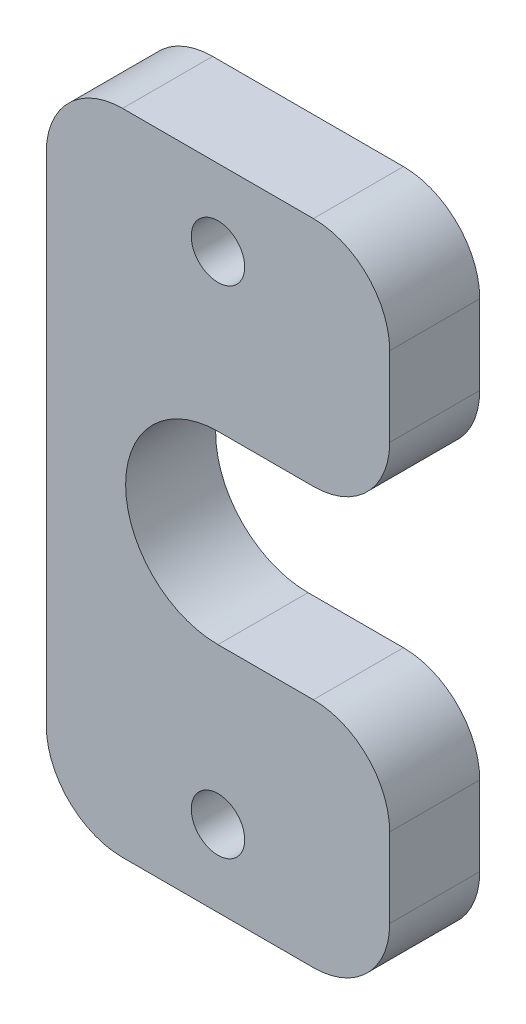
SolidWorks part; units mm, degrees
ref_plane "前视基准面" through (0, 0, 0) normal (0, 0, 1) x (1, 0, 0)
ref_plane "上视基准面" through (0, 0, 0) normal (0, 1, 0) x (1, 0, 0)
ref_plane "右视基准面" through (0, 0, 0) normal (1, 0, 0) x (0, 0, -1)
sketch "草图1" plane through (0, 0, 0) normal (0, 0, 1) x (1, 0, 0)
  line B0 (-11.25, 16.25) -> (-11.25, -16.25)
  line B1 (11.25, 16.25) -> (11.25, 11.05)
  line B2 (11.25, -11.05) -> (11.25, -16.25)
  line B3 (-6.25, 21.25) -> (6.25, 21.25)
  line B4 (-6.25, -21.25) -> (6.25, -21.25)
  line B5 (0, 6.05) -> (6.25, 6.05)
  line B6 (0, -6.05) -> (6.25, -6.05)
  arc B7 (6.25, 6.05) -> (11.25, 11.05) centre (6.25, 11.05) ccw
  arc B8 (11.25, -11.05) -> (6.25, -6.05) centre (6.25, -11.05) ccw
  circle B9 centre (0, 16.25) radius 1.75
  arc B10 (-6.25, 21.25) -> (-11.25, 16.25) centre (-6.25, 16.25) ccw
  arc B11 (11.25, 16.25) -> (6.25, 21.25) centre (6.25, 16.25) ccw
  circle B12 centre (0, -16.25) radius 1.75
  arc B13 (-11.25, -16.25) -> (-6.25, -21.25) centre (-6.25, -16.25) ccw
  arc B14 (6.25, -21.25) -> (11.25, -16.25) centre (6.25, -16.25) ccw
  arc B15 (0, 6.05) -> (0, -6.05) centre (0, 0) ccw
sketch_block_instance "块1-1"
sketch_block "块1"
extrude "凸台-拉伸1" add sketch "草图1" along normal blind 5.9
sketch "草图2" plane through (0, 0, 0) normal (0, 0, -1) x (-1, 0, 0)
  line L1 (1.6454, 13.4) -> (3.2909, 16.25)
  line L2 (3.2909, 16.25) -> (1.6454, 19.1)
  line L3 (1.6454, 19.1) -> (-1.6454, 19.1)
  line L4 (-1.6454, 19.1) -> (-3.2909, 16.25)
  line L5 (-3.2909, 16.25) -> (-1.6454, 13.4)
  line L6 (-1.6454, 13.4) -> (1.6454, 13.4)
  line L7 (-1.6454, -13.4) -> (-3.2909, -16.25)
  line L8 (-3.2909, -16.25) -> (-1.6454, -19.1)
  line L9 (-1.6454, -19.1) -> (1.6454, -19.1)
  line L10 (1.6454, -19.1) -> (3.2909, -16.25)
  line L11 (3.2909, -16.25) -> (1.6454, -13.4)
  line L12 (1.6454, -13.4) -> (-1.6454, -13.4)
  circle A0 centre (0, 16.25) radius 2.85 construction
  circle A1 centre (0, -16.25) radius 2.85 construction
  dimension "D1" = 5.7
  dimension "D2" = 5.7
extrude "切除-拉伸1" cut sketch "草图2" against normal blind 2.5
